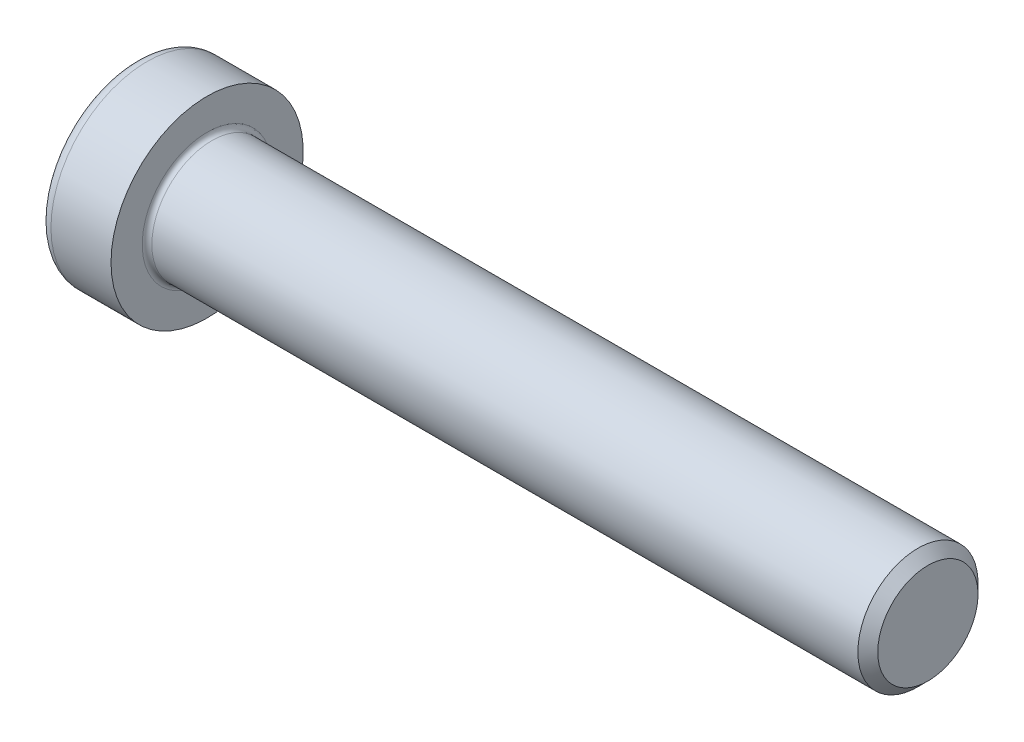
SolidWorks part; units mm, degrees
revolve "Base-Revolve" add sketch "BodySke"
sketch "BodySke" plane through (0, 0, 0) normal (0, 0, 1) x (1, 0, 0)
  line L0 (0, 0) -> (0, 8)
  line L1 (0, 8) -> (6, 8)
  line L2 (6, 8) -> (6, 5)
  line L3 (6, 5) -> (65.172, 5)
  line L4 (66, 4.172) -> (66, 0)
  line L5 (66, 0) -> (0, 0)
  line L6 (-31.75, 0) -> (127, 0) construction
  line L8 (66, 4.172) -> (65.172, 5)
  line L10 (66, -4.172) -> (65.172, -5) construction
  line L11 (7.5, 4.525) -> (7.5, -1.825) construction
  line L12 (40, 4.525) -> (40, -1.825) construction
  line L13 (6, 4.525) -> (6, -1.825) construction
  dimension "Head_ht" = 6
  dimension "Length" = 60
  dimension "Body_ch_ang" = 45
  dimension "Diameter" = 10
  dimension "Minor_dia" = 8.344
  dimension "Advance" = 1.5
  dimension "Thread_nom" = 26
  dimension "Thread_length" = 60
  dimension "Head_dia" = 16
cosmetic thread "ThreadCosmetic"
fillet "Fillet1" radius 0.4 1 edges at (6, 0, 5)
fillet "Fillet2" radius 1 1 edges at (0, 0, 8)
material "AISI 316 Нержавеющая сталь, лист (SS)"
ref_plane "Plane1" through (0, 0, 0) normal (0, 0, 1) x (1, 0, 0)
ref_plane "Plane2" through (0, 0, 0) normal (0, 1, 0) x (1, 0, 0)
ref_plane "Plane3" through (0, 0, 0) normal (1, 0, 0) x (0, 0, -1)
other "Configuration Table"
sketch "Sketch2" plane through (0, 0, 0) normal (0, 0, 1) x (1, 0, 0)
  line L0 (0, 3.5) -> (4.5, 3.5)
  line L1 (4.5, 3.5) -> (6.5207, 0)
  line L2 (-31.75, 0) -> (127, 0) construction
  line L3 (6.5207, 0) -> (0, 0)
  line L4 (0, 0) -> (0, 3.5)
  line L6 (0, 0) -> (47.625, 0) construction
  dimension "D1" = 3.5
  dimension "D2" = 60
  dimension "Depth" = 4.5
revolve "Hex-PreBroach" cut sketch "Sketch2" angle 360 about L6
sketch "Sketch3" plane through (0, 0, 0) normal (-1, 0, 0) x (0, 0.5, 0.866)
  line L0 (2.0207, 3.5) -> (-2.0207, 3.5)
  line L1 (-2.0207, 3.5) -> (-4.0415, 0)
  line L2 (2.0207, 3.5) -> (4.0415, 0)
  line L3 (2.0207, -3.5) -> (4.0415, 0)
  line L4 (2.0207, -3.5) -> (-2.0207, -3.5)
  line L5 (-2.0207, -3.5) -> (-4.0415, 0)
  dimension "D1" = 3.5
  dimension "D2" = 3.5
  dimension "Hex_size" = 7
extrude "Hex" cut sketch "Sketch3" against normal blind 4.5
sketch "ThdSchSke" plane through (0, 0, 0) normal (0, 0, 1) x (1, 0, 0)
  line L0 (40, -4.172) -> (39.4202, -5)
  line L1 (40, -4.172) -> (40.5798, -5)
  line L2 (40.5798, -5) -> (40.5798, -6.25)
  line L3 (-3.175, 0) -> (5.1513, 0) construction
  line L4 (0, 7) -> (0, -7) construction
  line L5 (40.5798, -6.25) -> (39.4202, -6.25)
  line L6 (39.4202, -6.25) -> (39.4202, -5)
  dimension "Thread_minor" = 8.344
  dimension "Diameter" = 10
  dimension "Start" = 40
revolve "ThreadSchematic" [suppressed] cut sketch "ThdSchSke" angle 360 about L3
pattern_linear "ThdSchPat" [suppressed]
equation "\"D2@Sketch3\" = \"Hex_size@Sketch3\" / 2"
equation "\"D1@Sketch3\" = \"Hex_size@Sketch3\" / 2"
equation "\"D1@Sketch2\" = \"Hex_size@Sketch3\" / 2"
equation "\"Thread_minor@ThreadCosmetic\"  =  \"Minor_dia@BodySke\""
equation "\"Depth@Sketch2\" =  \"Key_eng@Hex\""
equation "\"Thread_length@ThreadCosmetic\" = ((sgn( (\"Length@BodySke\" - \"Advance@BodySke\" * 3.0) - \"Thread_nom@BodySke\" )-1)*( (\"Length@BodySke\" - \"Advance@BodySke\" * 3.0) - \"Thread_nom@BodySke\" ))/-2+ \"Thread_nom@BodySke\""
equation "\"Thread_minor@ThdSchSke\" = \"Minor_dia@BodySke\""
equation "\"Diameter@ThdSchSke\" = \"Diameter@BodySke\""
equation "\"Overcut@ThdSchSke\" = \"Diameter@BodySke\" * 1.25"
equation "\"Start@ThdSchSke\" = \"Head_ht@BodySke\" + \"Length@BodySke\" - \"Thread_length@ThreadCosmetic\"  '---Non-countersunk---"
equation "\"Num_threads@ThdSchPat\" = int( \"Thread_length@ThreadCosmetic\" / \"Advance@BodySke\" + 0.999 )  + 1"
equation "\"Advance@ThdSchPat\" = \"Thread_length@ThreadCosmetic\" /  (\"Num_threads@ThdSchPat\" - 1) 'relax it"
equation "\"Num_threads@ThdSchPat\" = \"Num_threads@ThdSchPat\" - sgn( \"Num_threads@ThdSchPat\" - 1) '---chamfered tips only---"
